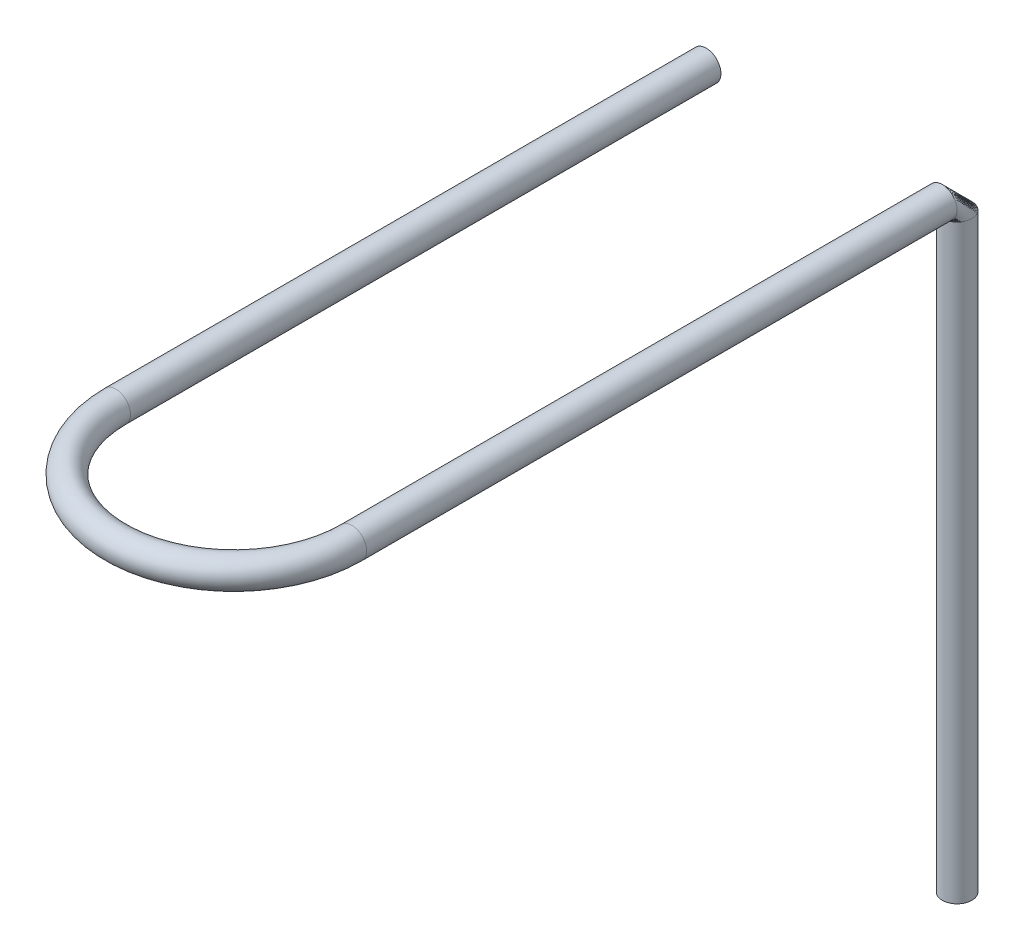
SolidWorks part; units mm, degrees
ref_plane "Plano frontal" through (0, 0, 0) normal (0, 0, 1) x (1, 0, 0)
ref_plane "Plano superior" through (0, 0, 0) normal (0, 1, 0) x (1, 0, 0)
ref_plane "Plano direito" through (0, 0, 0) normal (1, 0, 0) x (0, 0, -1)
sketch "Esboço1" plane through (0, 0, 0) normal (0, 1, 0) x (1, 0, 0)
  line L0 (0, 0) -> (0, -10)
  line L1 (-4, -10) -> (-4, 0)
  arc A0 (0, -10) -> (-4, -10) centre (-2, -10) cw
  point P5 (-4, -1.5203)
  dimension "D2" = 2
  dimension "D1" = 10
sketch "Esboço2" plane through (0, 0, 0) normal (1, 0, 0) x (0, 0, -1)
  line L0 (0.25, -0.25) -> (0.25, -10.25)
  arc A0 (0, 0) -> (0.25, -0.25) centre (0, -0.25) cw
  dimension "D2" = 0.25
  dimension "D1" = 10
sweep "Varredura1" add path "Esboço1" circular profile diameter 0.5 parameters "D3"=0.5
sweep "Varredura2" add path "Esboço2" circular profile diameter 0.5 parameters "D3"=0.5
